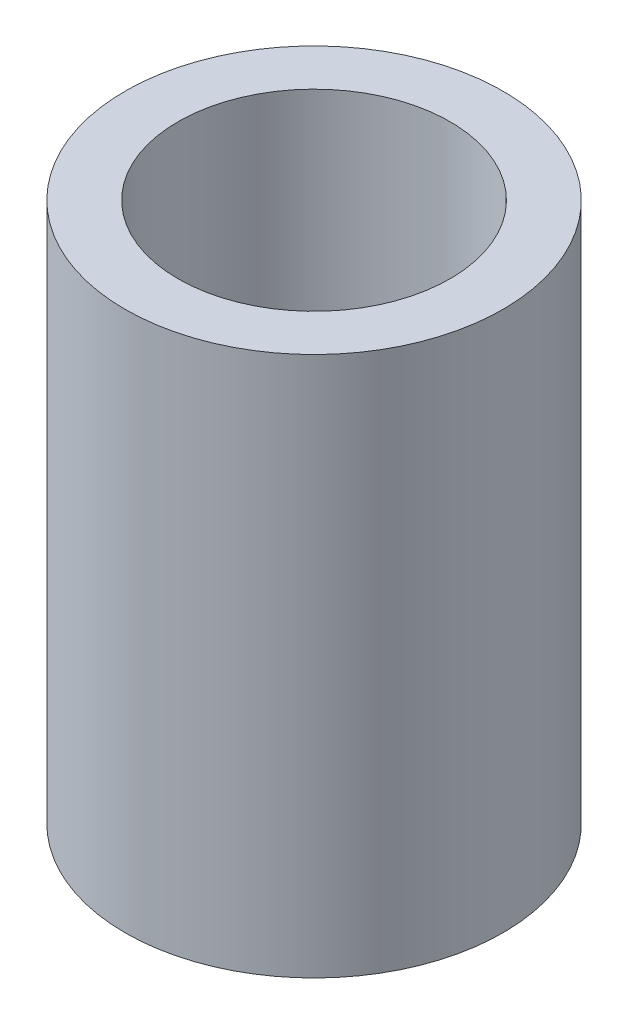
SolidWorks part; units mm, degrees
material "6061-T6 (SS)"
ref_plane "Front Plane" through (0, 0, 0) normal (0, 0, 1) x (1, 0, 0)
ref_plane "Top Plane" through (0, 0, 0) normal (0, 1, 0) x (1, 0, 0)
ref_plane "Right Plane" through (0, 0, 0) normal (1, 0, 0) x (0, 0, -1)
sketch "Sketch1" plane through (0, 0, 0) normal (0, 1, 0) x (1, 0, 0)
  circle A0 centre (0, 0) radius 4.445
  circle A1 centre (0, 0) radius 3.2004
  dimension "D1" = 8.89
  dimension "D2" = 6.4008
extrude "Boss-Extrude1" add sketch "Sketch1" along normal mid plane 12.7
